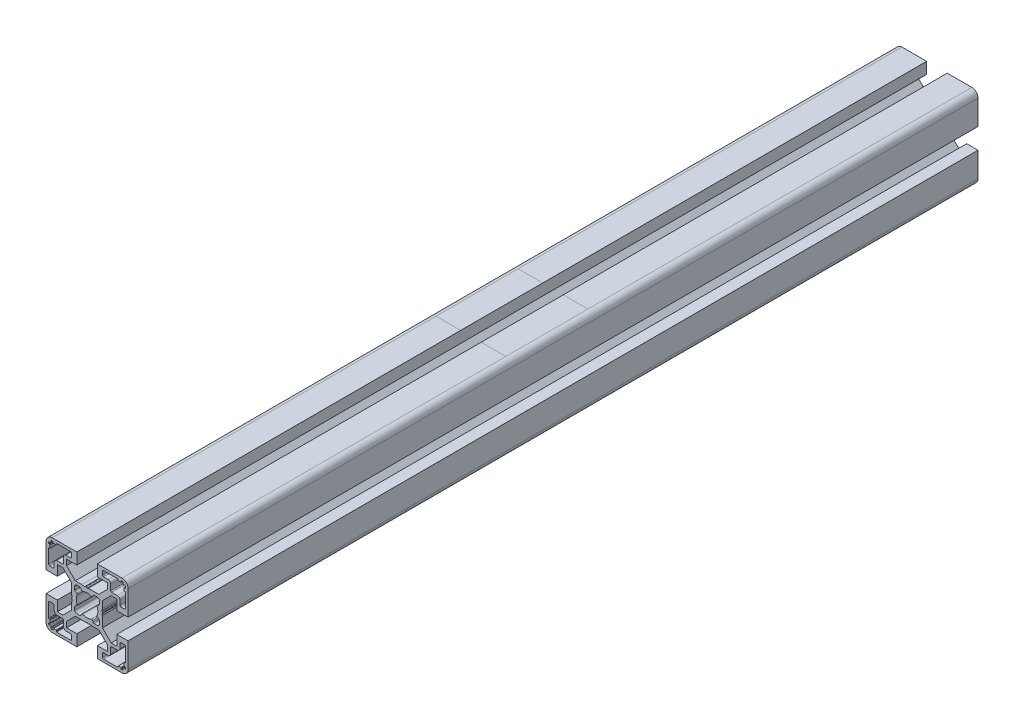
SolidWorks part; units mm, degrees
material "6063-T5"
ref_plane "Front Plane" through (0, 0, 0) normal (0, 0, 1) x (1, 0, 0)
ref_plane "Top Plane" through (0, 0, 0) normal (0, 1, 0) x (1, 0, 0)
ref_plane "Right Plane" through (0, 0, 0) normal (1, 0, 0) x (0, 0, -1)
ref_plane "Plan1" through (0, 0, 50) normal (0, 0, 1) x (1, 0, 0)
sketch "Esquisse1" plane through (0, 0, 50) normal (0, 0, 1) x (1, 0, 0)
  line L0 (-11.2645, -4.6769) -> (-11.2645, 2.1231)
  line L1 (-10.7645, 2.6231) -> (-9.0645, 2.6231)
  line L2 (-8.5645, 2.1231) -> (-8.5645, -0.0769)
  line L3 (-7.2645, -1.3769) -> (-4.5645, -1.3769)
  line L4 (-4.0645, -1.8769) -> (-4.0645, -4.5769)
  line L5 (-2.7645, -5.8769) -> (-0.5645, -5.8769)
  line L6 (-0.0645, -6.3769) -> (-0.0645, -8.0769)
  line L7 (-0.5645, -8.5769) -> (-7.3645, -8.5769)
  line L8 (-7.5645, -8.3769) -> (-7.5645, -8.0769)
  line L9 (-7.7645, -7.8769) -> (-8.9645, -7.8769)
  line L10 (-9.1645, -8.0769) -> (-9.1645, -8.3769)
  line L11 (-9.3645, -8.5769) -> (-9.8645, -8.5769)
  line L12 (-10.1645, -8.2769) -> (-10.1645, -7.7769)
  line L13 (-10.4645, -7.4769) -> (-10.9645, -7.4769)
  line L14 (-11.2645, -7.1769) -> (-11.2645, -6.6769)
  line L15 (-11.0645, -6.4769) -> (-10.7645, -6.4769)
  line L16 (-10.5645, -6.2769) -> (-10.5645, -5.0769)
  line L17 (-10.7645, -4.8769) -> (-11.0645, -4.8769)
  line L18 (14.9355, -8.0769) -> (14.9355, -6.3769)
  line L19 (15.4355, -5.8769) -> (17.6355, -5.8769)
  line L20 (18.9355, -4.5769) -> (18.9355, -1.8769)
  line L21 (19.4355, -1.3769) -> (22.1355, -1.3769)
  line L22 (23.4355, -0.0769) -> (23.4355, 2.1231)
  line L23 (23.9355, 2.6231) -> (25.6355, 2.6231)
  line L24 (26.1355, 2.1231) -> (26.1355, -4.6769)
  line L25 (25.9355, -4.8769) -> (25.6355, -4.8769)
  line L26 (25.4355, -5.0769) -> (25.4355, -6.2769)
  line L27 (25.6355, -6.4769) -> (25.9355, -6.4769)
  line L28 (26.1355, -6.6769) -> (26.1355, -7.1769)
  line L29 (25.8355, -7.4769) -> (25.3355, -7.4769)
  line L30 (25.0355, -7.7769) -> (25.0355, -8.2769)
  line L31 (24.7355, -8.5769) -> (24.2355, -8.5769)
  line L32 (24.0355, -8.3769) -> (24.0355, -8.0769)
  line L33 (23.8355, -7.8769) -> (22.6355, -7.8769)
  line L34 (22.4355, -8.0769) -> (22.4355, -8.3769)
  line L35 (22.2355, -8.5769) -> (15.4355, -8.5769)
  line L36 (-12.5645, 27.1231) -> (-12.5645, 15.1231)
  line L37 (-12.5645, 15.1231) -> (-7.0645, 15.1231)
  line L38 (-7.0645, 15.1231) -> (-7.0645, 20.1231)
  line L39 (-7.0645, 20.1231) -> (-4.3322, 20.1231)
  line L40 (-4.3322, 20.1231) -> (-0.0645, 15.8553)
  line L41 (-0.0645, 15.8553) -> (-0.0645, 10.7767)
  line L42 (0.0025, 10.5267) -> (0.2355, 10.1231)
  line L43 (0.2355, 10.1231) -> (0.0025, 9.7195)
  line L44 (0.0025, 9.2195) -> (0.1846, 8.9042)
  line L45 (0.1846, 8.9042) -> (-0.0645, 7.6231)
  line L46 (-0.0645, 7.6231) -> (-0.0645, 4.3908)
  line L47 (-0.0645, 4.3908) -> (-4.3322, 0.1231)
  line L48 (-4.3322, 0.1231) -> (-7.0645, 0.1231)
  line L49 (-7.0645, 0.1231) -> (-7.0645, 5.1231)
  line L50 (-7.0645, 5.1231) -> (-12.5645, 5.1231)
  line L51 (-12.5645, 5.1231) -> (-12.5645, -6.8769)
  line L52 (-9.5645, -9.8769) -> (2.4355, -9.8769)
  line L53 (2.4355, -9.8769) -> (2.4355, -4.3769)
  line L54 (2.4355, -4.3769) -> (-2.5645, -4.3769)
  line L55 (-2.5645, -4.3769) -> (-2.5645, -1.6447)
  line L56 (-2.5645, -1.6447) -> (1.7033, 2.6231)
  line L57 (1.7033, 2.6231) -> (6.7819, 2.6231)
  line L58 (7.0319, 2.6901) -> (7.4355, 2.9231)
  line L59 (7.4355, 2.9231) -> (7.8391, 2.6901)
  line L60 (8.3391, 2.6901) -> (8.6544, 2.8721)
  line L61 (8.6544, 2.8721) -> (9.9355, 2.6231)
  line L62 (9.9355, 2.6231) -> (13.1678, 2.6231)
  line L63 (13.1678, 2.6231) -> (17.4355, -1.6447)
  line L64 (17.4355, -1.6447) -> (17.4355, -4.3769)
  line L65 (17.4355, -4.3769) -> (12.4355, -4.3769)
  line L66 (12.4355, -4.3769) -> (12.4355, -9.8769)
  line L67 (12.4355, -9.8769) -> (24.4355, -9.8769)
  line L68 (27.4355, -6.8769) -> (27.4355, 5.1231)
  line L69 (27.4355, 5.1231) -> (21.9355, 5.1231)
  line L70 (21.9355, 5.1231) -> (21.9355, 0.1231)
  line L71 (21.9355, 0.1231) -> (19.2033, 0.1231)
  line L72 (19.2033, 0.1231) -> (14.9355, 4.3908)
  line L73 (14.9355, 4.3908) -> (14.9355, 9.4695)
  line L74 (14.8686, 9.7195) -> (14.6355, 10.1231)
  line L75 (14.6355, 10.1231) -> (14.8686, 10.5267)
  line L76 (14.8686, 11.0267) -> (14.6865, 11.342)
  line L77 (14.6865, 11.342) -> (14.9355, 12.6231)
  line L78 (14.9355, 12.6231) -> (14.9355, 15.8553)
  line L79 (14.9355, 15.8553) -> (19.2033, 20.1231)
  line L80 (19.2033, 20.1231) -> (21.9355, 20.1231)
  line L81 (21.9355, 20.1231) -> (21.9355, 15.1231)
  line L82 (21.9355, 15.1231) -> (27.4355, 15.1231)
  line L83 (27.4355, 15.1231) -> (27.4355, 27.1231)
  line L84 (24.4355, 30.1231) -> (12.4355, 30.1231)
  line L85 (12.4355, 30.1231) -> (12.4355, 24.6231)
  line L86 (12.4355, 24.6231) -> (17.4355, 24.6231)
  line L87 (17.4355, 24.6231) -> (17.4355, 21.8908)
  line L88 (17.4355, 21.8908) -> (13.1678, 17.6231)
  line L89 (13.1678, 17.6231) -> (8.0891, 17.6231)
  line L90 (7.8391, 17.5561) -> (7.4355, 17.3231)
  line L91 (7.4355, 17.3231) -> (7.0319, 17.5561)
  line L92 (6.5319, 17.5561) -> (6.2167, 17.3741)
  line L93 (6.2167, 17.3741) -> (4.9355, 17.6231)
  line L94 (4.9355, 17.6231) -> (1.7033, 17.6231)
  line L95 (1.7033, 17.6231) -> (-2.5645, 21.8908)
  line L96 (-2.5645, 21.8908) -> (-2.5645, 24.6231)
  line L97 (-2.5645, 24.6231) -> (2.4355, 24.6231)
  line L98 (2.4355, 24.6231) -> (2.4355, 30.1231)
  line L99 (2.4355, 30.1231) -> (-9.5645, 30.1231)
  line L100 (14.9355, 26.6231) -> (14.9355, 28.3231)
  line L101 (15.4355, 28.8231) -> (22.2355, 28.8231)
  line L102 (22.4355, 28.6231) -> (22.4355, 28.3231)
  line L103 (22.6355, 28.1231) -> (23.8355, 28.1231)
  line L104 (24.0355, 28.3231) -> (24.0355, 28.6231)
  line L105 (24.2355, 28.8231) -> (24.7355, 28.8231)
  line L106 (25.0355, 28.5231) -> (25.0355, 28.0231)
  line L107 (25.3355, 27.7231) -> (25.8355, 27.7231)
  line L108 (26.1355, 27.4231) -> (26.1355, 26.9231)
  line L109 (25.9355, 26.7231) -> (25.6355, 26.7231)
  line L110 (25.4355, 26.5231) -> (25.4355, 25.3231)
  line L111 (25.6355, 25.1231) -> (25.9355, 25.1231)
  line L112 (26.1355, 24.9231) -> (26.1355, 18.1231)
  line L113 (25.6355, 17.6231) -> (23.9355, 17.6231)
  line L114 (23.4355, 18.1231) -> (23.4355, 20.3231)
  line L115 (22.1355, 21.6231) -> (19.4355, 21.6231)
  line L116 (18.9355, 22.1231) -> (18.9355, 24.8231)
  line L117 (17.6355, 26.1231) -> (15.4355, 26.1231)
  line L118 (-11.2645, 18.1231) -> (-11.2645, 24.9231)
  line L119 (-11.0645, 25.1231) -> (-10.7645, 25.1231)
  line L120 (-10.5645, 25.3231) -> (-10.5645, 26.5231)
  line L121 (-10.7645, 26.7231) -> (-11.0645, 26.7231)
  line L122 (-11.2645, 26.9231) -> (-11.2645, 27.4231)
  line L123 (-10.9645, 27.7231) -> (-10.4645, 27.7231)
  line L124 (-10.1645, 28.0231) -> (-10.1645, 28.5231)
  line L125 (-9.8645, 28.8231) -> (-9.3645, 28.8231)
  line L126 (-9.1645, 28.6231) -> (-9.1645, 28.3231)
  line L127 (-8.9645, 28.1231) -> (-7.7645, 28.1231)
  line L128 (-7.5645, 28.3231) -> (-7.5645, 28.6231)
  line L129 (-7.3645, 28.8231) -> (-0.5645, 28.8231)
  line L130 (-0.0645, 28.3231) -> (-0.0645, 26.6231)
  line L131 (-0.5645, 26.1231) -> (-2.7645, 26.1231)
  line L132 (-4.0645, 24.8231) -> (-4.0645, 22.1231)
  line L133 (-4.5645, 21.6231) -> (-7.2645, 21.6231)
  line L134 (-8.5645, 20.3231) -> (-8.5645, 18.1231)
  line L135 (-9.0645, 17.6231) -> (-10.7645, 17.6231)
  line L136 (10.9262, 16.1231) -> (12.4355, 16.1231)
  line L137 (13.4355, 15.1231) -> (13.4355, 13.6138)
  line L138 (13.1703, 13.1723) -> (12.4933, 12.8123)
  line L139 (12.4933, 7.4338) -> (13.1703, 7.0739)
  line L140 (13.4355, 6.6324) -> (13.4355, 5.1231)
  line L141 (12.4355, 4.1231) -> (10.9262, 4.1231)
  line L142 (10.4848, 4.3883) -> (10.1248, 5.0654)
  line L143 (4.7463, 5.0654) -> (4.3863, 4.3883)
  line L144 (3.9449, 4.1231) -> (2.4355, 4.1231)
  line L145 (1.4355, 5.1231) -> (1.4355, 6.6324)
  line L146 (1.7008, 7.0739) -> (2.3778, 7.4338)
  line L147 (2.3778, 12.8123) -> (1.7008, 13.1723)
  line L148 (1.4355, 13.6138) -> (1.4355, 15.1231)
  line L149 (2.4355, 16.1231) -> (3.9449, 16.1231)
  line L150 (4.3863, 15.8578) -> (4.7463, 15.1808)
  line L151 (10.1248, 15.1808) -> (10.4848, 15.8578)
  arc A0 (-11.2645, 2.1231) -> (-10.7645, 2.6231) centre (-10.7645, 2.1231) cw
  arc A1 (-9.0645, 2.6231) -> (-8.5645, 2.1231) centre (-9.0645, 2.1231) cw
  arc A2 (-8.5645, -0.0769) -> (-7.2645, -1.3769) centre (-7.2645, -0.0769) ccw
  arc A3 (-4.5645, -1.3769) -> (-4.0645, -1.8769) centre (-4.5645, -1.8769) cw
  arc A4 (-4.0645, -4.5769) -> (-2.7645, -5.8769) centre (-2.7645, -4.5769) ccw
  arc A5 (-0.5645, -5.8769) -> (-0.0645, -6.3769) centre (-0.5645, -6.3769) cw
  arc A6 (-0.0645, -8.0769) -> (-0.5645, -8.5769) centre (-0.5645, -8.0769) cw
  arc A7 (-7.3645, -8.5769) -> (-7.5645, -8.3769) centre (-7.3645, -8.3769) cw
  arc A8 (-7.5645, -8.0769) -> (-7.7645, -7.8769) centre (-7.7645, -8.0769) ccw
  arc A9 (-8.9645, -7.8769) -> (-9.1645, -8.0769) centre (-8.9645, -8.0769) ccw
  arc A10 (-9.1645, -8.3769) -> (-9.3645, -8.5769) centre (-9.3645, -8.3769) cw
  arc A11 (-9.8645, -8.5769) -> (-10.1645, -8.2769) centre (-9.8645, -8.2769) cw
  arc A12 (-10.1645, -7.7769) -> (-10.4645, -7.4769) centre (-10.4645, -7.7769) ccw
  arc A13 (-10.9645, -7.4769) -> (-11.2645, -7.1769) centre (-10.9645, -7.1769) cw
  arc A14 (-11.2645, -6.6769) -> (-11.0645, -6.4769) centre (-11.0645, -6.6769) cw
  arc A15 (-10.7645, -6.4769) -> (-10.5645, -6.2769) centre (-10.7645, -6.2769) ccw
  arc A16 (-10.5645, -5.0769) -> (-10.7645, -4.8769) centre (-10.7645, -5.0769) ccw
  arc A17 (-11.0645, -4.8769) -> (-11.2645, -4.6769) centre (-11.0645, -4.6769) cw
  arc A18 (14.9355, -6.3769) -> (15.4355, -5.8769) centre (15.4355, -6.3769) cw
  arc A19 (17.6355, -5.8769) -> (18.9355, -4.5769) centre (17.6355, -4.5769) ccw
  arc A20 (18.9355, -1.8769) -> (19.4355, -1.3769) centre (19.4355, -1.8769) cw
  arc A21 (22.1355, -1.3769) -> (23.4355, -0.0769) centre (22.1355, -0.0769) ccw
  arc A22 (23.4355, 2.1231) -> (23.9355, 2.6231) centre (23.9355, 2.1231) cw
  arc A23 (25.6355, 2.6231) -> (26.1355, 2.1231) centre (25.6355, 2.1231) cw
  arc A24 (26.1355, -4.6769) -> (25.9355, -4.8769) centre (25.9355, -4.6769) cw
  arc A25 (25.6355, -4.8769) -> (25.4355, -5.0769) centre (25.6355, -5.0769) ccw
  arc A26 (25.4355, -6.2769) -> (25.6355, -6.4769) centre (25.6355, -6.2769) ccw
  arc A27 (25.9355, -6.4769) -> (26.1355, -6.6769) centre (25.9355, -6.6769) cw
  arc A28 (26.1355, -7.1769) -> (25.8355, -7.4769) centre (25.8355, -7.1769) cw
  arc A29 (25.3355, -7.4769) -> (25.0355, -7.7769) centre (25.3355, -7.7769) ccw
  arc A30 (25.0355, -8.2769) -> (24.7355, -8.5769) centre (24.7355, -8.2769) cw
  arc A31 (24.2355, -8.5769) -> (24.0355, -8.3769) centre (24.2355, -8.3769) cw
  arc A32 (24.0355, -8.0769) -> (23.8355, -7.8769) centre (23.8355, -8.0769) ccw
  arc A33 (22.6355, -7.8769) -> (22.4355, -8.0769) centre (22.6355, -8.0769) ccw
  arc A34 (22.4355, -8.3769) -> (22.2355, -8.5769) centre (22.2355, -8.3769) cw
  arc A35 (15.4355, -8.5769) -> (14.9355, -8.0769) centre (15.4355, -8.0769) cw
  arc A36 (-9.5645, 30.1231) -> (-12.5645, 27.1231) centre (-9.5645, 27.1231) ccw
  arc A37 (-0.0645, 10.7767) -> (0.0025, 10.5267) centre (0.4355, 10.7767) ccw
  arc A38 (0.0025, 9.7195) -> (0.0025, 9.2195) centre (0.4355, 9.4695) ccw
  arc A39 (-12.5645, -6.8769) -> (-9.5645, -9.8769) centre (-9.5645, -6.8769) ccw
  arc A40 (6.7819, 2.6231) -> (7.0319, 2.6901) centre (6.7819, 3.1231) ccw
  arc A41 (7.8391, 2.6901) -> (8.3391, 2.6901) centre (8.0891, 3.1231) ccw
  arc A42 (24.4355, -9.8769) -> (27.4355, -6.8769) centre (24.4355, -6.8769) ccw
  arc A43 (14.9355, 9.4695) -> (14.8686, 9.7195) centre (14.4355, 9.4695) ccw
  arc A44 (14.8686, 10.5267) -> (14.8686, 11.0267) centre (14.4355, 10.7767) ccw
  arc A45 (27.4355, 27.1231) -> (24.4355, 30.1231) centre (24.4355, 27.1231) ccw
  arc A46 (8.0891, 17.6231) -> (7.8391, 17.5561) centre (8.0891, 17.1231) ccw
  arc A47 (7.0319, 17.5561) -> (6.5319, 17.5561) centre (6.7819, 17.1231) ccw
  arc A48 (14.9355, 28.3231) -> (15.4355, 28.8231) centre (15.4355, 28.3231) cw
  arc A49 (22.2355, 28.8231) -> (22.4355, 28.6231) centre (22.2355, 28.6231) cw
  arc A50 (22.4355, 28.3231) -> (22.6355, 28.1231) centre (22.6355, 28.3231) ccw
  arc A51 (23.8355, 28.1231) -> (24.0355, 28.3231) centre (23.8355, 28.3231) ccw
  arc A52 (24.0355, 28.6231) -> (24.2355, 28.8231) centre (24.2355, 28.6231) cw
  arc A53 (24.7355, 28.8231) -> (25.0355, 28.5231) centre (24.7355, 28.5231) cw
  arc A54 (25.0355, 28.0231) -> (25.3355, 27.7231) centre (25.3355, 28.0231) ccw
  arc A55 (25.8355, 27.7231) -> (26.1355, 27.4231) centre (25.8355, 27.4231) cw
  arc A56 (26.1355, 26.9231) -> (25.9355, 26.7231) centre (25.9355, 26.9231) cw
  arc A57 (25.6355, 26.7231) -> (25.4355, 26.5231) centre (25.6355, 26.5231) ccw
  arc A58 (25.4355, 25.3231) -> (25.6355, 25.1231) centre (25.6355, 25.3231) ccw
  arc A59 (25.9355, 25.1231) -> (26.1355, 24.9231) centre (25.9355, 24.9231) cw
  arc A60 (26.1355, 18.1231) -> (25.6355, 17.6231) centre (25.6355, 18.1231) cw
  arc A61 (23.9355, 17.6231) -> (23.4355, 18.1231) centre (23.9355, 18.1231) cw
  arc A62 (23.4355, 20.3231) -> (22.1355, 21.6231) centre (22.1355, 20.3231) ccw
  arc A63 (19.4355, 21.6231) -> (18.9355, 22.1231) centre (19.4355, 22.1231) cw
  arc A64 (18.9355, 24.8231) -> (17.6355, 26.1231) centre (17.6355, 24.8231) ccw
  arc A65 (15.4355, 26.1231) -> (14.9355, 26.6231) centre (15.4355, 26.6231) cw
  arc A66 (-11.2645, 24.9231) -> (-11.0645, 25.1231) centre (-11.0645, 24.9231) cw
  arc A67 (-10.7645, 25.1231) -> (-10.5645, 25.3231) centre (-10.7645, 25.3231) ccw
  arc A68 (-10.5645, 26.5231) -> (-10.7645, 26.7231) centre (-10.7645, 26.5231) ccw
  arc A69 (-11.0645, 26.7231) -> (-11.2645, 26.9231) centre (-11.0645, 26.9231) cw
  arc A70 (-11.2645, 27.4231) -> (-10.9645, 27.7231) centre (-10.9645, 27.4231) cw
  arc A71 (-10.4645, 27.7231) -> (-10.1645, 28.0231) centre (-10.4645, 28.0231) ccw
  arc A72 (-10.1645, 28.5231) -> (-9.8645, 28.8231) centre (-9.8645, 28.5231) cw
  arc A73 (-9.3645, 28.8231) -> (-9.1645, 28.6231) centre (-9.3645, 28.6231) cw
  arc A74 (-9.1645, 28.3231) -> (-8.9645, 28.1231) centre (-8.9645, 28.3231) ccw
  arc A75 (-7.7645, 28.1231) -> (-7.5645, 28.3231) centre (-7.7645, 28.3231) ccw
  arc A76 (-7.5645, 28.6231) -> (-7.3645, 28.8231) centre (-7.3645, 28.6231) cw
  arc A77 (-0.5645, 28.8231) -> (-0.0645, 28.3231) centre (-0.5645, 28.3231) cw
  arc A78 (-0.0645, 26.6231) -> (-0.5645, 26.1231) centre (-0.5645, 26.6231) cw
  arc A79 (-2.7645, 26.1231) -> (-4.0645, 24.8231) centre (-2.7645, 24.8231) ccw
  arc A80 (-4.0645, 22.1231) -> (-4.5645, 21.6231) centre (-4.5645, 22.1231) cw
  arc A81 (-7.2645, 21.6231) -> (-8.5645, 20.3231) centre (-7.2645, 20.3231) ccw
  arc A82 (-8.5645, 18.1231) -> (-9.0645, 17.6231) centre (-9.0645, 18.1231) cw
  arc A83 (-10.7645, 17.6231) -> (-11.2645, 18.1231) centre (-10.7645, 18.1231) cw
  arc A84 (12.4355, 16.1231) -> (13.4355, 15.1231) centre (12.4355, 15.1231) cw
  arc A85 (13.4355, 13.6138) -> (13.1703, 13.1723) centre (12.9355, 13.6138) cw
  arc A86 (12.4933, 12.8123) -> (12.2678, 12.1754) centre (12.728, 12.3708) ccw
  arc A87 (12.2678, 12.1754) -> (12.2678, 8.0708) centre (7.4355, 10.1231) cw
  arc A88 (12.2678, 8.0708) -> (12.4933, 7.4338) centre (12.728, 7.8753) ccw
  arc A89 (13.1703, 7.0739) -> (13.4355, 6.6324) centre (12.9355, 6.6324) cw
  arc A90 (13.4355, 5.1231) -> (12.4355, 4.1231) centre (12.4355, 5.1231) cw
  arc A91 (10.9262, 4.1231) -> (10.4848, 4.3883) centre (10.9262, 4.6231) cw
  arc A92 (10.1248, 5.0654) -> (9.4878, 5.2908) centre (9.6833, 4.8306) ccw
  arc A93 (9.4878, 5.2908) -> (5.3832, 5.2908) centre (7.4355, 10.1231) cw
  arc A94 (5.3832, 5.2908) -> (4.7463, 5.0654) centre (5.1878, 4.8306) ccw
  arc A95 (4.3863, 4.3883) -> (3.9449, 4.1231) centre (3.9449, 4.6231) cw
  arc A96 (2.4355, 4.1231) -> (1.4355, 5.1231) centre (2.4355, 5.1231) cw
  arc A97 (1.4355, 6.6324) -> (1.7008, 7.0739) centre (1.9355, 6.6324) cw
  arc A98 (2.3778, 7.4338) -> (2.6033, 8.0708) centre (2.1431, 7.8753) ccw
  arc A99 (2.6033, 8.0708) -> (2.6033, 12.1754) centre (7.4355, 10.1231) cw
  arc A100 (2.6033, 12.1754) -> (2.3778, 12.8123) centre (2.1431, 12.3708) ccw
  arc A101 (1.7008, 13.1723) -> (1.4355, 13.6138) centre (1.9355, 13.6138) cw
  arc A102 (1.4355, 15.1231) -> (2.4355, 16.1231) centre (2.4355, 15.1231) cw
  arc A103 (3.9449, 16.1231) -> (4.3863, 15.8578) centre (3.9449, 15.6231) cw
  arc A104 (4.7463, 15.1808) -> (5.3832, 14.9553) centre (5.1878, 15.4155) ccw
  arc A105 (5.3832, 14.9553) -> (9.4878, 14.9553) centre (7.4355, 10.1231) cw
  arc A106 (9.4878, 14.9553) -> (10.1248, 15.1808) centre (9.6833, 15.4155) ccw
  arc A107 (10.4848, 15.8578) -> (10.9262, 16.1231) centre (10.9262, 15.6231) cw
extrude "Boss.-Extru.1" add sketch "Esquisse1" against normal blind 414
sketch "Esquisse2" plane through (0, 30.1231, 0) normal (0, 1, 0) x (1, 0, 0)
  line L0 (-12.5645, 364) -> (-12.5645, -50) construction
  line L1 (-12.5645, 177) -> (27.4355, 177)
  line L2 (-12.5645, 177) -> (-12.5645, 137)
  line L3 (-12.5645, 137) -> (27.4355, 137)
  line L4 (27.4355, 177) -> (27.4355, 137)
  line L5 (27.4355, 364) -> (27.4355, -50) construction
  line L6 (-12.5645, 157) -> (27.4355, 157) construction
  dimension "D1" = 40
split line "Ligne de séparation1"
